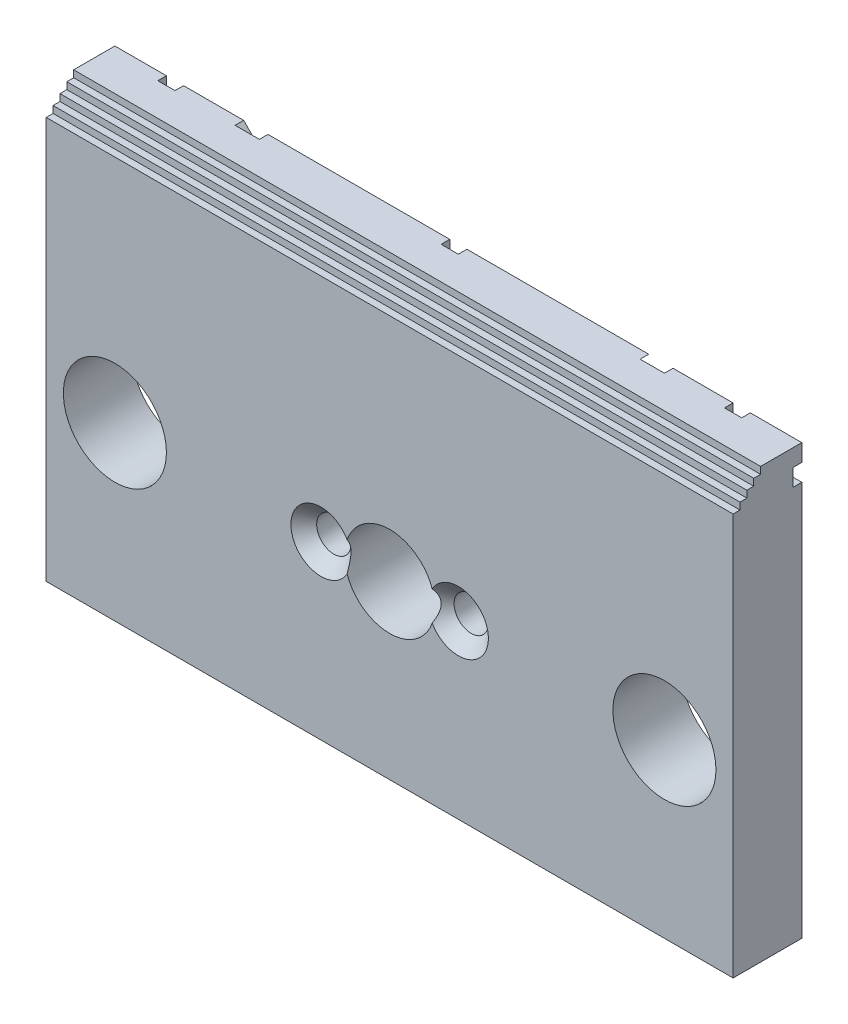
SolidWorks part; units mm, degrees
ref_plane "前视基准面" through (0, 0, 0) normal (0, 0, 1) x (1, 0, 0)
ref_plane "上视基准面" through (0, 0, 0) normal (0, 1, 0) x (1, 0, 0)
ref_plane "右视基准面" through (0, 0, 0) normal (1, 0, 0) x (0, 0, -1)
other "Configuration Table"
ref_plane "基准面1" through (0, 0, 1) normal (0, 0, -1) x (-1, 0, 0)
sketch "草图1" plane through (0, 0, 1) normal (0, 0, -1) x (-1, 0, 0)
  line L0 (-80, -13.3333) -> (0, -13.3333)
  line L1 (0, -13.3333) -> (0, 46.6667)
  line L2 (0, 46.6667) -> (-80, 46.6667)
  line L3 (-80, 46.6667) -> (-80, -13.3333)
  dimension "D1" = 80
  dimension "D2" = 60
extrude "凸台-拉伸1" add sketch "草图1" against normal blind 8
hole_wizard "Ø12.0 (12) 直径孔1" positions "草图21" profile "草图20" hole size "Ø12.0" standard "ANSI Metric" end condition through all
sketch "草图21" plane through (0, 0, 9) normal (0, 0, 1) x (1, 0, 0)
  line L0 (80, 16.6667) -> (0, 16.6667) construction
  line L1 (80, 46.6667) -> (80, -13.3333) construction
  line L2 (0, -13.3333) -> (0, 46.6667) construction
  line L3 (0, 46.6667) -> (80, 46.6667) construction
  point P0 (72, 16.6667)
  point P1 (8, 16.6667)
  dimension "D1" = 8
  dimension "D2" = 8
  dimension "D3" = 30
sketch "草图20" plane through (72, 16.6667, 9) normal (1, 0, 0) x (0, -1, 0)
  line L0 (0, 0) -> (0, 8)
  line L1 (0, 8) -> (6, 8)
  line L2 (6, 8) -> (6, 0)
  line L5 (6, 0) -> (0, 0)
  line L11 (0, -6.35) -> (0, 107.95) construction
  dimension "通孔孔直径" = 12
  dimension "通孔孔深度" = 8
hole_wizard "Ø10.5 (10.5) 直径孔1" positions "草图23" profile "草图22" hole size "Ø10.5" standard "ANSI Metric" end condition through all
sketch "草图23" plane through (0, 0, 1) normal (0, 0, -1) x (-1, 0, 0)
  line L0 (-80, 16.6667) -> (0, 16.6667) construction
  line L3 (0, 46.6667) -> (-80, 46.6667) construction
  point P0 (-40, 16.6667)
  dimension "D1" = 30
sketch "草图22" plane through (40, 16.6667, 1) normal (1, 0, 0) x (0, 1, 0)
  line L0 (0, 0) -> (0, 8)
  line L1 (0, 8) -> (5.25, 8)
  line L2 (5.25, 8) -> (5.25, 0)
  line L5 (5.25, 0) -> (0, 0)
  line L11 (0, -6.35) -> (0, 107.95) construction
  dimension "通孔孔直径" = 10.5
  dimension "通孔孔深度" = 8
hole_wizard "M3.5 平头机械螺钉的锥形沉头孔1" positions "草图25" profile "草图24" countersink size "M3.5" standard "ANSI Metric" end condition through all
sketch "草图25" plane through (0, 0, 9) normal (0, 0, 1) x (1, 0, 0)
  line L0 (0, 16.6667) -> (80, 16.6667) construction
  line L3 (0, 46.6667) -> (80, 46.6667) construction
  point P0 (32, 16.6667)
  point P1 (48, 16.6667)
  point P10 (40, 16.6667)
  dimension "D1" = 16
  dimension "D2" = 8
  dimension "D3" = 30
sketch "草图24" plane through (32, 16.6667, 9) normal (1, 0, 0) x (0, -1, 0)
  line L0 (0, 0) -> (0, 8)
  line L1 (0, 8) -> (2, 8)
  line L2 (2, 8) -> (2, 1.5)
  line L3 (2, 1.5) -> (3.5, 0)
  line L5 (3.5, 0) -> (0, 0)
  line L6 (-2, 1.5) -> (-3.5, 0) construction
  line L11 (0, -6.35) -> (0, 107.95) construction
  dimension "通孔孔直径" = 4
  dimension "通孔孔深度" = 8
  dimension "近端锥形沉头孔直径" = 7
  dimension "近端锥形沉头孔角度" = 90
sketch "草图27" plane through (0, 0, 1) normal (0, 0, -1) x (-1, 0, 0)
  line L0 (-40, 46.6667) -> (-40, -13.3333) construction
  line L1 (0, 46.6667) -> (-80, 46.6667) construction
  line L2 (-80, -13.3333) -> (0, -13.3333) construction
  line L3 (-80, 46.6667) -> (-80, -13.3333) construction
  line L4 (-80, 44.6667) -> (0, 44.6667)
  line L5 (-80, 44.6667) -> (-80, 42.6667)
  line L6 (-80, 42.6667) -> (0, 42.6667)
  line L7 (-40, 44.6667) -> (-40, 42.6667)
  line L8 (-80, 30.6667) -> (0, 30.6667) construction
  line L9 (-74, 46.6667) -> (-72, 46.6667)
  line L10 (-74, 46.6667) -> (-74, 30.6667)
  line L11 (-74, 30.6667) -> (-72, 30.6667)
  line L12 (-72, 46.6667) -> (-72, 30.6667)
  line L13 (-41, 46.6667) -> (-39, 46.6667)
  line L14 (-41, 46.6667) -> (-41, 30.6667)
  line L15 (-41, 30.6667) -> (-39, 30.6667)
  line L16 (-40, 46.6667) -> (-40, 30.6667)
  line L17 (0, -13.3333) -> (0, 46.6667) construction
  line L18 (-65, 46.6667) -> (-49, 30.6667)
  line L23 (-49, 30.6667) -> (-47.5858, 32.0809)
  line L24 (-47.5858, 32.0809) -> (-63.5858, 48.0809)
  line L25 (-63.5858, 48.0809) -> (-65, 46.6667)
  line L26 (-39, 46.6667) -> (-39, 30.6667)
  line L27 (-32.4142, 32.0809) -> (-16.4142, 48.0809)
  line L28 (-31, 30.6667) -> (-32.4142, 32.0809)
  line L29 (-15, 46.6667) -> (-31, 30.6667)
  line L30 (-16.4142, 48.0809) -> (-15, 46.6667)
  line L31 (-6, 30.6667) -> (-8, 30.6667)
  line L32 (-8, 46.6667) -> (-8, 30.6667)
  line L33 (-6, 46.6667) -> (-8, 46.6667)
  line L34 (-6, 46.6667) -> (-6, 30.6667)
  line L35 (0, 44.6667) -> (0, 42.6667)
  circle A0 centre (-73, 30.6667) radius 1
  circle A1 centre (-48.2929, 31.3738) radius 1
  circle A2 centre (-40, 30.6667) radius 1
  circle A3 centre (-31.7071, 31.3738) radius 1
  circle A4 centre (-7, 30.6667) radius 1
  line M27 (-80, 46.6667) -> (-80, -13.3333)
  line M29 (0, -13.3333) -> (0, 46.6667)
  dimension "D1" = 16
  dimension "D2" = 2
  dimension "D3" = 2
  dimension "D4" = 2
  dimension "D5" = 2
  dimension "D6" = 45
  dimension "D7" = 1
  dimension "D8" = 6
  dimension "D9" = 7
extrude "切除-拉伸1" cut sketch "草图27" against normal blind 1 contours L4 L34 L6 M29 | L32 L4 L29 L6 | L6 L27 L4 L26 | L24 L6 L14 L4 | L18 L4 L12 L6 | L10 L4 L6 M27 | A0 | A1 | A2 | A3 | A4
sketch "草图28" plane through (0, 0, 0) normal (-1, 0, 0) x (0, 0, 1)
  line L0 (9, 46.6667) -> (5.8, 46.6667)
  line L1 (9, 46.6667) -> (1, 46.6667) construction
  line L2 (5.8, 46.6667) -> (5.8, 45.8667)
  line L3 (5.8, 45.8667) -> (6.6, 45.8667)
  line L4 (6.6, 45.8667) -> (6.6, 45.0667)
  line L5 (6.6, 45.0667) -> (7.4, 45.0667)
  line L6 (7.4, 45.0667) -> (7.4, 44.2667)
  line L7 (7.4, 44.2667) -> (8.2, 44.2667)
  line L8 (8.2, 44.2667) -> (8.2, 43.4667)
  line L9 (8.2, 43.4667) -> (9, 43.4667)
  line L10 (9, -13.3333) -> (9, 46.6667) construction
  line L11 (9, 46.6667) -> (9, 43.4667)
  dimension "D1" = 0.8
  dimension "D2" = 0.8
  dimension "D3" = 0.8
  dimension "D4" = 0.8
  dimension "D5" = 0.8
  dimension "D6" = 0.8
  dimension "D7" = 0.8
  dimension "D8" = 0.8
extrude "切除-拉伸2" cut sketch "草图28" against normal up to next
sketch "草图29" plane through (0, 0, 1) normal (0, 0, -1) x (-1, 0, 0)
  line L0 (0, -13.3333) -> (0, 42.6667) construction
  line L1 (-80, -13.3333) -> (0, -13.3333)
  line L2 (-80, -13.3333) -> (-80, -3.3333)
  line L3 (-80, -3.3333) -> (0, -3.3333)
  line L4 (0, -13.3333) -> (0, -3.3333)
  dimension "D1" = 10
extrude "切除-拉伸3" cut sketch "草图29" against normal up to next
